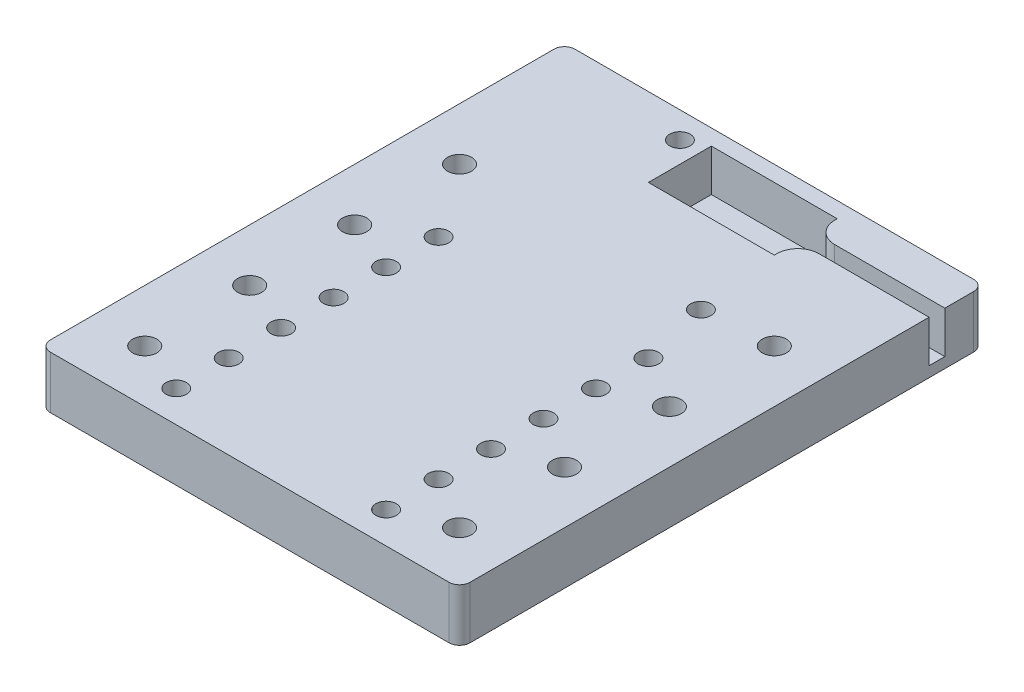
SolidWorks part; units mm, degrees
ref_plane "Front Plane" through (0, 0, 0) normal (0, 0, 1) x (1, 0, 0)
ref_plane "Top Plane" through (0, 0, 0) normal (0, 1, 0) x (1, 0, 0)
ref_plane "Right Plane" through (0, 0, 0) normal (1, 0, 0) x (0, 0, -1)
sketch "Sketch1" plane through (0, 0, 0) normal (0, 1, 0) x (1, 0, 0)
  line L0 (0, 0) -> (0, -25) construction
  line L1 (-20, -25) -> (20, -25)
  line L2 (-20, -25) -> (-20, 25)
  line L3 (-20, 25) -> (20, 25)
  line L4 (20, -25) -> (20, 25)
  line L5 (-20, -25) -> (20, 25) construction
  line L6 (-20, 25) -> (20, -25) construction
  point P0 (0, 0)
  point P6 (0, 0)
  dimension "D4" = 40
  dimension "D6" = 50
extrude "Boss-Extrude1" add sketch "Sketch1" along normal blind 5
sketch "Sketch9" plane through (0, 5, 0) normal (0, 1, 0) x (1, 0, 0)
  line L0 (0, 0) -> (0, 25) construction
  line L1 (20, 25) -> (-20, 25) construction
  line L2 (0, 0) -> (-15, 0) construction
  circle A0 centre (-15, 0) radius 1.15
  circle A1 centre (15, 0) radius 1.15
  dimension "D2" = 2.3
  dimension "D1" = 30
extrude "Cut-Extrude8" cut sketch "Sketch9" against normal through all
pattern_linear "LPattern2" count 3 spacing 10 along (0, 0, 1) count 2 spacing 10 along (0, 0, -1) of "Cut-Extrude8"
sketch "Sketch4" plane through (0, 5, 0) normal (0, 1, 0) x (1, 0, 0)
  line L0 (11, 16) -> (0, 16) construction
  line L1 (-6.5, 9.5) -> (8.5, 9.5) construction
  line L2 (-6.5, 9.5) -> (-6.5, 22.5) construction
  line L3 (-6.5, 22.5) -> (8.5, 22.5) construction
  line L4 (8.5, 9.5) -> (8.5, 22.5) construction
  line L5 (-6.5, 9.5) -> (8.5, 22.5) construction
  line L6 (-6.5, 22.5) -> (8.5, 9.5) construction
  line L7 (-9, 7) -> (11, 7) construction
  line L8 (-9, 7) -> (-9, 25) construction
  line L9 (-9, 25) -> (11, 25) construction
  line L10 (11, 7) -> (11, 25) construction
  line L11 (-9, 7) -> (11, 25) construction
  line L12 (-9, 25) -> (11, 7) construction
  line L13 (0, 16) -> (0, 0) construction
  line L14 (20, 25) -> (-20, 25) construction
  circle A0 centre (-6.5, 22.5) radius 0.975
  circle A2 centre (8.5, 9.5) radius 0.975
  point P0 (1, 16)
  point P9 (1, 16)
  dimension "D1" = 1.95
  dimension "D2" = 15
  dimension "D3" = 13
  dimension "D4" = 20
  dimension "D5" = 18
  dimension "D6" = 11
extrude "Cut-Extrude3" cut sketch "Sketch4" against normal through all
sketch "Sketch5" plane through (0, 5, 0) normal (0, 1, 0) x (1, 0, 0)
  line L0 (0, 0) -> (0, -25) construction
  line L1 (-20, -25) -> (20, -25) construction
  circle A0 centre (-10, -22) radius 0.975
  circle A1 centre (10, -22) radius 0.975
  dimension "D3" = 1.95
  dimension "D1" = 20
  dimension "D2" = 3
extrude "Cut-Extrude4" cut sketch "Sketch5" against normal through all
pattern_linear "LPattern1" count 6 spacing 5 along (0, 0, -1) of "Cut-Extrude4"
fillet "Fillet1" radius 1 4 edges at (-20, 2.5, -25) (-20, 2.5, 25) (20, 2.5, 25) (20, 2.5, -25)
sketch "Sketch8" plane through (0, 5, 0) normal (0, 1, 0) x (1, 0, 0)
  line L0 (7.5, 23.5) -> (7.5, 21.25)
  line L1 (-4.5, 23.5) -> (7.5, 23.5)
  line L2 (-4.5, 23.5) -> (-4.5, 17.5)
  line L3 (-4.5, 17.5) -> (7.5, 17.5)
  line L4 (7.5, 23.5) -> (7.5, 17.5) construction
  line L5 (7.5, 21.25) -> (20, 21.25)
  line L6 (20, -24) -> (20, 24) construction
  line L7 (20, 21.25) -> (20, 19.75)
  line L8 (20, 19.75) -> (7.5, 19.75)
  line L9 (7.5, 19.75) -> (7.5, 17.5)
  line L10 (19, 25) -> (-19, 25) construction
  dimension "D1" = 4.5
  dimension "D2" = 7.5
  dimension "D3" = 6
  dimension "D5" = 1.5
  dimension "D7" = 1.5
extrude "Cut-Extrude7" cut sketch "Sketch8" against normal offset from surface (4 mm away) 1 up to face at (-10, 0, 17.975)
fillet "Fillet2" radius 2 2 edges at (7.5, 3, -19.75) (7.5, 3, -21.25)
